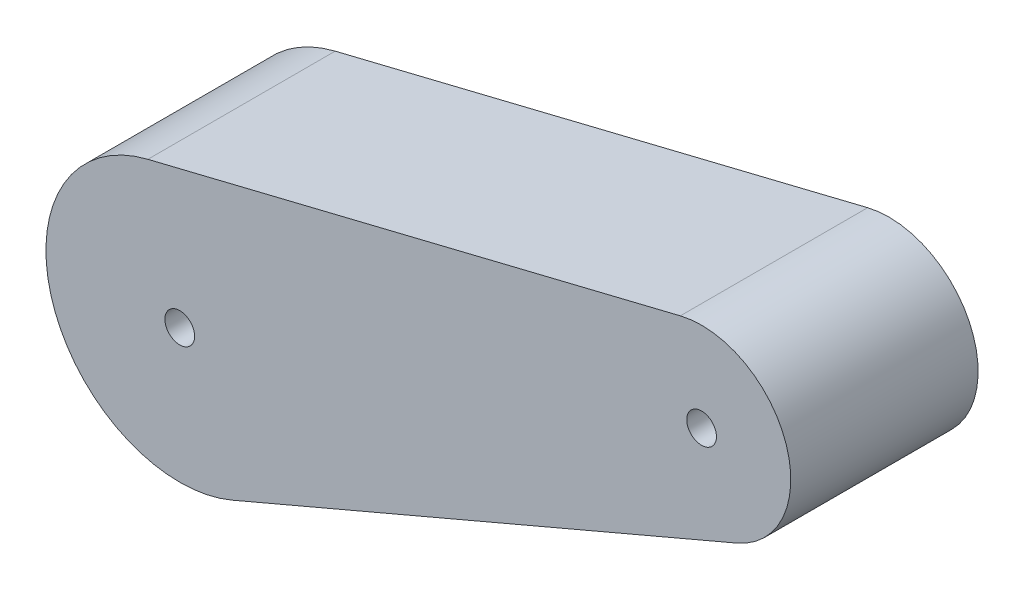
SolidWorks part; units mm, degrees
ref_plane "前基準面" through (0, 0, 0) normal (0, 0, 1) x (1, 0, 0)
ref_plane "上基準面" through (0, 0, 0) normal (0, 1, 0) x (1, 0, 0)
ref_plane "右基準面" through (0, 0, 0) normal (1, 0, 0) x (0, 0, -1)
sketch "草圖1" plane through (0, 0, 0) normal (0, 0, 1) x (1, 0, 0)
  line L0 (-10.7241, 43.7035) -> (168.3543, 87.6461)
  line L1 (17.6468, -41.3955) -> (187.2681, 30.9134)
  line L2 (0, 0) -> (175.5036, 58.5105) construction
  arc A0 (-10.7241, 43.7035) -> (17.6468, -41.3955) centre (0, 0) ccw
  arc A1 (187.2681, 30.9134) -> (168.3543, 87.6461) centre (175.5036, 58.5105) ccw
  circle A2 centre (175.5036, 58.5105) radius 5
  circle A3 centre (0, 0) radius 5
  dimension "D1" = 90
  dimension "D3" = 60
  dimension "D2" = 185
extrude "Boss-Extrude1" add sketch "草圖1" along normal mid plane 63
